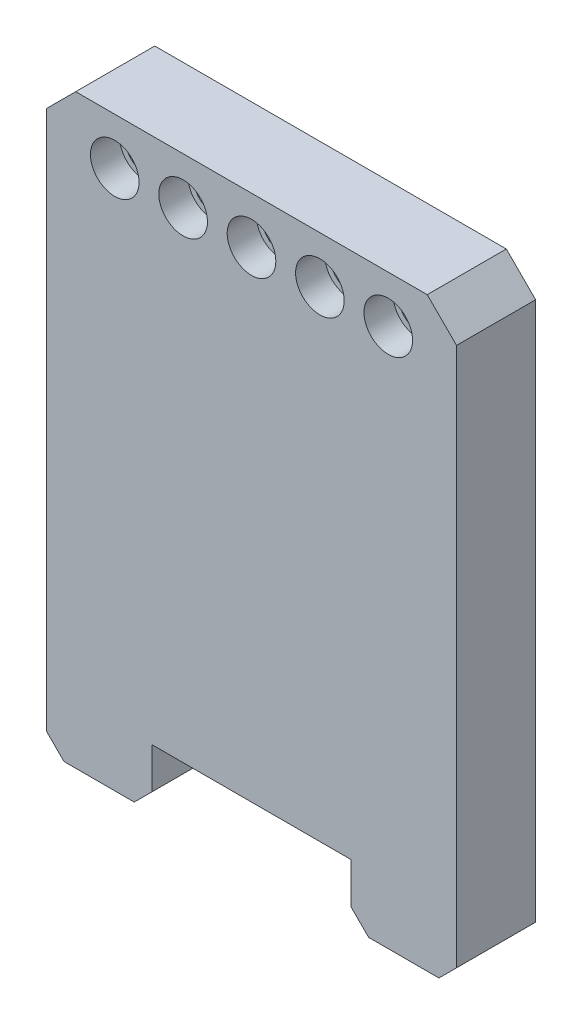
SolidWorks part; units mm, degrees
ref_plane "Front Plane" through (0, 0, 0) normal (0, 0, 1) x (1, 0, 0)
ref_plane "Top Plane" through (0, 0, 0) normal (0, 1, 0) x (1, 0, 0)
ref_plane "Right Plane" through (0, 0, 0) normal (1, 0, 0) x (0, 0, -1)
sketch "Sketch1" plane through (0, 0, 0) normal (0, 1, 0) x (1, 0, 0)
  line L1 (-35, 6.75) -> (35, 6.75)
  line L2 (-35, 6.75) -> (-35, -6.75)
  line L3 (-35, -6.75) -> (35, -6.75)
  line L4 (35, 6.75) -> (35, -6.75)
  line L5 (-35, 6.75) -> (35, -6.75) construction
  line L6 (-35, -6.75) -> (35, 6.75) construction
  point P0 (0, 0)
  dimension "D1" = 70
  dimension "D2" = 13.5
extrude "Boss-Extrude1" add sketch "Sketch1" along normal mid plane 100
sketch "Sketch2" plane through (0, 0, 6.75) normal (0, 0, 1) x (1, 0, 0)
  line L0 (-35, -50) -> (35, -50) construction
  line L1 (-17, -50) -> (17, -50)
  line L2 (-17, -50) -> (-17, -40)
  line L3 (-17, -40) -> (17, -40)
  line L4 (17, -50) -> (17, -40)
  point P6 (0, -40)
  dimension "D1" = 34
  dimension "D2" = 10
extrude "Cut-Extrude1" cut sketch "Sketch2" against normal blind 100
sketch "Sketch3" plane through (0, -40, 0) normal (0, -1, 0) x (1, 0, 0)
  line L0 (-10, 0) -> (10, 0) construction
  circle A0 centre (-10, 0) radius 3.225
  circle A1 centre (0, 0) radius 3.225
  circle A2 centre (10, 0) radius 3.225
  dimension "D1" = 6.45
  dimension "D2" = 20
extrude "Cut-Extrude2" cut sketch "Sketch3" against normal blind 3
chamfer "Chamfer1" distance 0.5 angle 45 3 edges at (10, -40, -3.225) (0, -40, -3.225) (-10, -40, -3.225)
sketch "Sketch4" plane through (0, 0, 6.75) normal (0, 0, 1) x (1, 0, 0)
  line L0 (-35, 50) -> (35, 50) construction
  line L1 (-35, 50) -> (-35, -50) construction
  line L2 (35, 50) -> (35, -50) construction
  circle A0 centre (-23.33, 42) radius 4.15
  circle A1 centre (-11.66, 42) radius 4.15
  circle A2 centre (0.01, 42) radius 4.15
  circle A3 centre (11.68, 42) radius 4.15
  circle A4 centre (23.35, 42) radius 4.15
  dimension "D1" = 8.3
  dimension "D2" = 8
  dimension "D3" = 11.67
  dimension "D5" = 11.65
  dimension "D4" = 5
extrude "Cut-Extrude3" cut sketch "Sketch4" against normal blind 5
sketch "Sketch5" plane through (0, 0, 1.75) normal (0, 0, 1) x (1, 0, 0)
  circle A0 centre (-23.33, 42) radius 3.15
  circle A1 centre (-11.66, 42) radius 3.15
  circle A2 centre (0.01, 42) radius 3.15
  circle A3 centre (11.68, 42) radius 3.15
  circle A4 centre (23.35, 42) radius 3.15
  dimension "D1" = 6.3
  dimension "D3" = 11.67
  dimension "D2" = 5
extrude "Cut-Extrude4" cut sketch "Sketch5" against normal blind 3
chamfer "Chamfer2" distance 3 angle 45 4 edges at (17, -50, 0) (-17, -50, 0) (35, -50, 0) (-35, -50, 0)
chamfer "Chamfer3" distance 5 angle 45 2 edges at (35, 50, 0) (-35, 50, 0)
